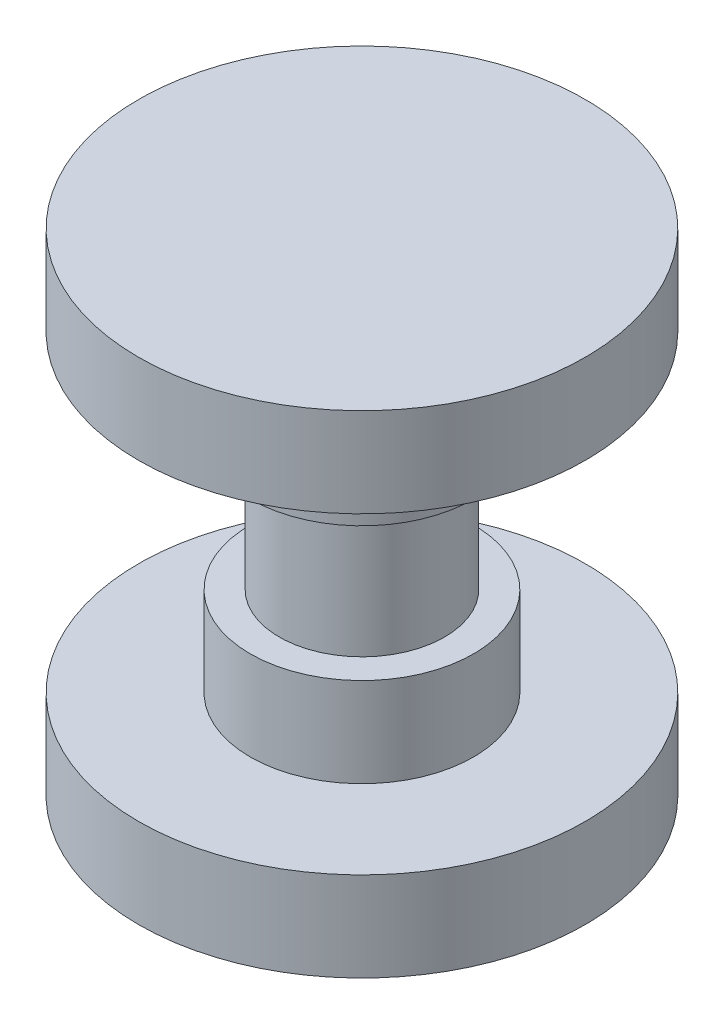
SolidWorks part; units mm, degrees
material "Nylon 6/10 edit"
ref_plane "Front Plane" through (0, 0, 0) normal (0, 0, 1) x (1, 0, 0)
ref_plane "Top Plane" through (0, 0, 0) normal (0, 1, 0) x (1, 0, 0)
ref_plane "Right Plane" through (0, 0, 0) normal (1, 0, 0) x (0, 0, -1)
sketch "Sketch1" plane through (0, 0, 0) normal (0, 1, 0) x (1, 0, 0)
  circle A0 centre (0, 0) radius 31.75
  dimension "D1" = 63.5
extrude "Boss-Extrude1" add sketch "Sketch1" along normal blind 12.7
sketch "Sketch2" plane through (0, 12.7, 0) normal (0, 1, 0) x (1, 0, 0)
  circle A0 centre (0, 0) radius 15.875
  dimension "D1" = 31.75
extrude "Boss-Extrude2" add sketch "Sketch2" along normal blind 12.7
sketch "Sketch4" plane through (0, 25.4, 0) normal (0, 1, 0) x (1, 0, 0)
  circle A0 centre (0, 0) radius 11.7475
  dimension "D1" = 23.495
extrude "Boss-Extrude4" add sketch "Sketch4" along normal blind 19.05
sketch "Sketch5" plane through (0, 44.45, 0) normal (0, 1, 0) x (1, 0, 0)
  circle A0 centre (0, 0) radius 15.875
extrude "Boss-Extrude5" add sketch "Sketch5" along normal blind 12.7
sketch "Sketch6" plane through (0, 57.15, 0) normal (0, 1, 0) x (1, 0, 0)
  circle A0 centre (0, 0) radius 31.75
extrude "Boss-Extrude6" add sketch "Sketch6" along normal blind 12.7
